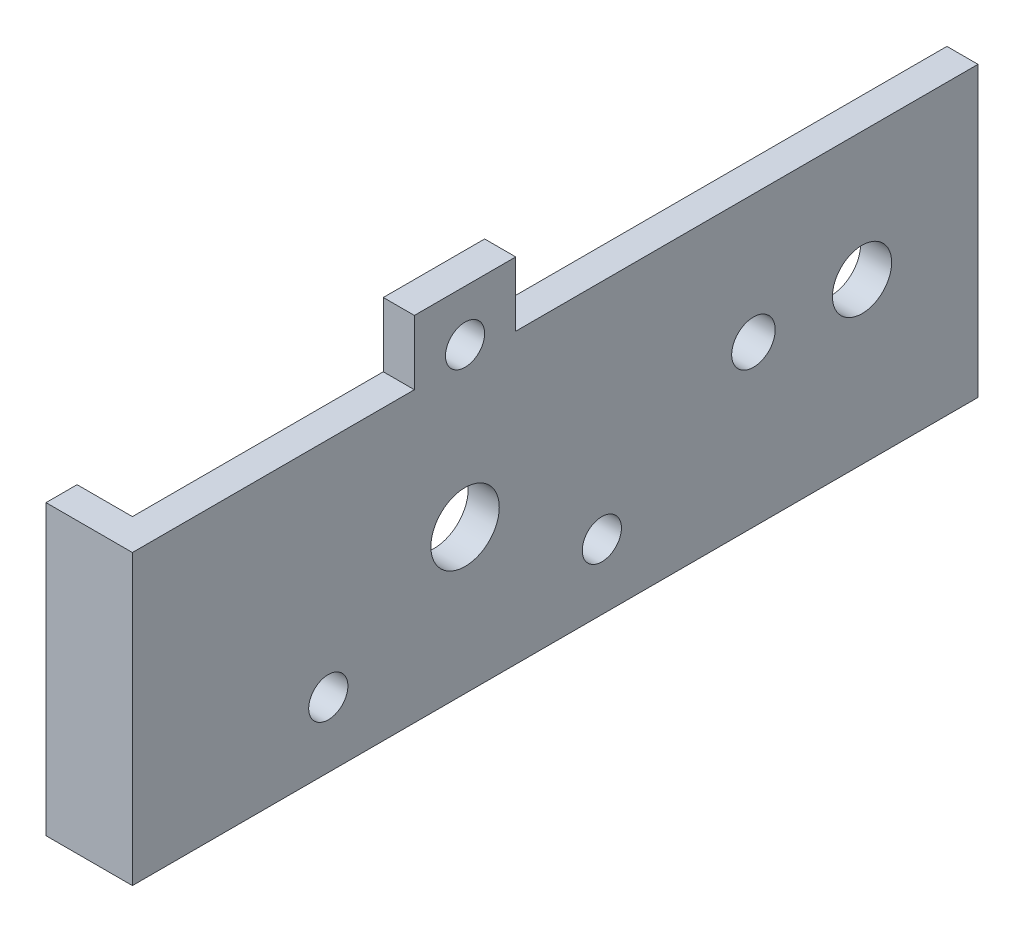
SolidWorks part; units mm, degrees
material "AISI 316 Stainless Steel Sheet (SS)"
ref_plane "Front Plane" through (0, 0, 0) normal (0, 0, 1) x (1, 0, 0)
ref_plane "Top Plane" through (0, 0, 0) normal (0, 1, 0) x (1, 0, 0)
ref_plane "Right Plane" through (0, 0, 0) normal (1, 0, 0) x (0, 0, -1)
sketch "Sketch8" plane through (0, 0, 0) normal (1, 0, 0) x (0, 0, -1)
  line L0 (63, 70.2) -> (68, 70.2)
  line L1 (68, 70.2) -> (68, 23.8)
  line L2 (68, 23.8) -> (63, 23.8)
  line L3 (63, 23.8) -> (63, 70.2)
  dimension "D1" = 5
  dimension "D3" = 46.4
extrude "Boss-Extrude6" add sketch "Sketch8" along normal blind 13.9
sketch "Sketch9" plane through (0, 0, -68) normal (0, 0, -1) x (-1, 0, 0)
  line L0 (-13.9, 70.2) -> (-8.9, 70.2)
  line L1 (-13.9, 70.2) -> (-13.9, 23.8)
  line L2 (-8.9, 70.2) -> (-8.9, 23.8)
  line L3 (-13.9, 23.8) -> (-8.9, 23.8)
  line L4 (-13.9, 23.8) -> (-13.9, 70.2) construction
  line L5 (-13.9, 70.2) -> (0, 70.2) construction
  line L7 (-13.9, 23.8) -> (0, 23.8) construction
  dimension "D1" = 5
extrude "Boss-Extrude7" add sketch "Sketch9" along normal blind 131
sketch "Sketch10" plane through (13.9, 0, 0) normal (1, 0, 0) x (0, 0, -1)
  line L1 (63, 23.8) -> (199, 23.8) construction
  line L2 (63, 70.2) -> (63, 23.8) construction
  circle A0 centre (116.5, 47) radius 5.5
  circle A1 centre (116.5, 72.4) radius 3.15
  circle A2 centre (138.497, 34.3) radius 3.15
  circle A3 centre (94.503, 34.3) radius 3.15
  circle A4 centre (116.5, 47) radius 25.4 construction
  dimension "D1" = 11
  dimension "D3" = 6.3
  dimension "D5" = 6.3
  dimension "D6" = 6.3
  dimension "D11" = 50.8
  dimension "D2" = 53.5
  dimension "D7" = 23.2
  dimension "D10" = 12.7
sketch "Sketch11" plane through (13.9, 0, 0) normal (1, 0, 0) x (0, 0, -1)
  line L0 (108.35, 70.2) -> (124.65, 70.2)
  line L1 (199, 70.2) -> (63, 70.2) construction
  line L2 (124.65, 70.2) -> (124.65, 80.55)
  line L3 (124.65, 80.55) -> (108.35, 80.55)
  line L4 (108.35, 80.55) -> (108.35, 70.2)
  dimension "D1" = 8.15
  dimension "D2" = 8.15
  dimension "D3" = 8.15
extrude "Boss-Extrude8" add sketch "Sketch11" against normal blind 5
extrude "Cut-Extrude2" cut sketch "Sketch10" against normal blind 5
sketch "Sketch16" plane through (13.9, 0, 0) normal (1, 0, 0) x (0, 0, -1)
  circle A0 centre (180.3485, 49.5625) radius 4.7625
extrude "Cut-Extrude6" cut sketch "Sketch16" against normal blind 9
sketch "Sketch17" plane through (13.9, 0, 0) normal (1, 0, 0) x (0, 0, -1)
  circle A0 centre (162.886, 49.5625) radius 3.5
  dimension "D1" = 7
extrude "Cut-Extrude7" cut sketch "Sketch17" against normal blind 9
sketch "Sketch18" plane through (0, 0, 0) normal (-1, 0, 0) x (0, 0, 1)
  line L0 (-68, 27) -> (-63, 27) construction
  line L1 (-68, 23.8) -> (-68, 70.2) construction
  line L2 (-63, 70.2) -> (-63, 23.8) construction
  line L3 (-63, 23.8) -> (-68, 23.8) construction
  line L4 (-68, 32) -> (-63, 32) construction
  line L5 (-68, 37) -> (-63, 37) construction
  line L6 (-68, 42) -> (-63, 42) construction
  line L7 (-68, 47) -> (-63, 47) construction
  line L8 (-68, 52) -> (-63, 52) construction
  line L9 (-68, 57) -> (-63, 57) construction
  line L10 (-68, 62) -> (-63, 62) construction
  line L11 (-68, 67) -> (-63, 67) construction
  line L12 (-68, 27) -> (-68, 32) construction
  line L13 (-65.5, 70.2) -> (-65.5, 23.8) construction
  line L14 (-68, 70.2) -> (-63, 70.2) construction
  dimension "D1" = 3.2
  dimension "D2" = 9
  dimension "D3" = 5
hole_wizard "M2.5x0.45 Tapped Hole1" positions "Sketch19" profile "Sketch20" tap size "M2.5x0.45" standard "ANSI Metric"
sketch "Sketch19" plane through (0, 0, 0) normal (-1, 0, 0) x (0, 0, 1)
  line L0 (-68, 62) -> (-63, 62) construction
  line L1 (-68, 52) -> (-63, 52) construction
  line L2 (-68, 32) -> (-63, 32) construction
  line L3 (-68, 42) -> (-63, 42) construction
  point P0 (-65.5, 62)
  point P4 (-65.5, 52)
  point P8 (-65.5, 32)
  point P12 (-65.5, 42)
cosmetic thread "Hole Thread1" parameters "D1"=11.5, "D2"=2.5
cosmetic thread "Hole Thread2" parameters "D1"=11.5, "D2"=2.5
cosmetic thread "Hole Thread3" parameters "D1"=11.5, "D2"=2.5
cosmetic thread "Hole Thread4" parameters "D1"=11.5, "D2"=2.5
sketch "Sketch20" plane through (0, 62, -65.5) normal (0, 1, 0) x (0, 0, 1)
  line L0 (0, 0) -> (0, 13.1159)
  line L1 (0, 13.1159) -> (1.025, 12.5)
  line L2 (1.025, 12.5) -> (1.025, 0.25)
  line L3 (1.025, 0.25) -> (1.275, 0)
  line L5 (1.275, 0) -> (0, 0)
  line L6 (-1.025, 0.25) -> (-1.275, 0) construction
  line L10 (0, 13.1159) -> (-1.025, 12.5) construction
  line L11 (0, -6.35) -> (0, 107.95) construction
  dimension "Tap Drill Dia." = 2.05
  dimension "Tap Drill Depth" = 12.5
  dimension "Near C'Sink Dia." = 2.55
  dimension "Near C'Sink Angle" = 90
  dimension "Drill Angle" = 118
